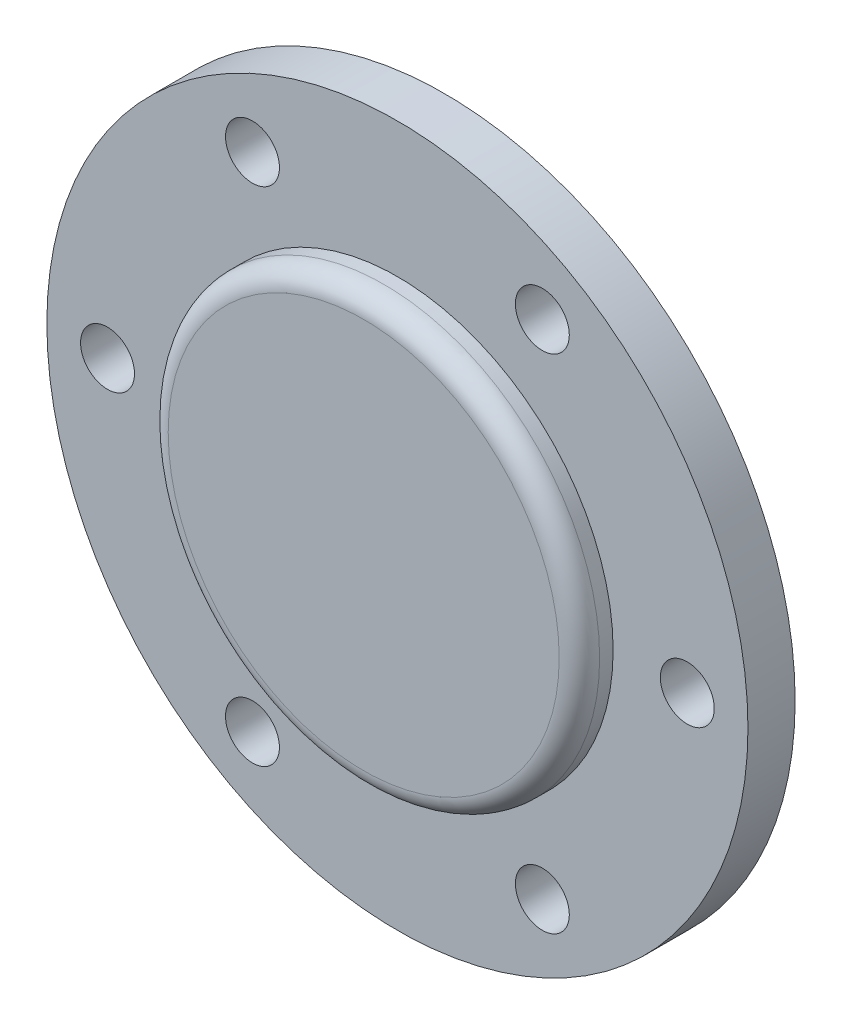
SolidWorks part; units mm, degrees
ref_plane "Front Plane" through (0, 0, 0) normal (0, 0, 1) x (1, 0, 0)
ref_plane "Top Plane" through (0, 0, 0) normal (0, 1, 0) x (1, 0, 0)
ref_plane "Right Plane" through (0, 0, 0) normal (1, 0, 0) x (0, 0, -1)
sketch "Sketch1" plane through (0, 0, 0) normal (0, 0, 1) x (1, 0, 0)
  circle A0 centre (0, 0) radius 26
  circle A1 centre (0, 0) radius 21.5 construction
  circle A2 centre (-21.5, 0) radius 2
  circle A3 centre (-10.75, 18.6195) radius 2
  circle A4 centre (10.75, 18.6195) radius 2
  circle A5 centre (21.5, 0) radius 2
  circle A6 centre (10.75, -18.6195) radius 2
  circle A7 centre (-10.75, -18.6195) radius 2
  point P18 (0, 0)
  dimension "D1" = 52
  dimension "D2" = 43
  dimension "D3" = 4
  dimension "D4" = 6
extrude "Boss-Extrude1" add sketch "Sketch1" along normal blind 3.5
sketch "Sketch2" plane through (0, 0, 3.5) normal (0, 0, 1) x (1, 0, 0)
  circle A0 centre (0, 0) radius 16
  dimension "D1" = 32
extrude "Boss-Extrude2" add sketch "Sketch2" along normal blind 2.5
fillet "Fillet1" radius 1.5 1 edges at (16, 0, 6)
sketch "Sketch3" plane through (0, 0, 0) normal (0, 0, -1) x (-1, 0, 0)
  circle A0 centre (0, 0) radius 15
  dimension "D1" = 30
extrude "Boss-Extrude3" add sketch "Sketch3" along normal blind 1
